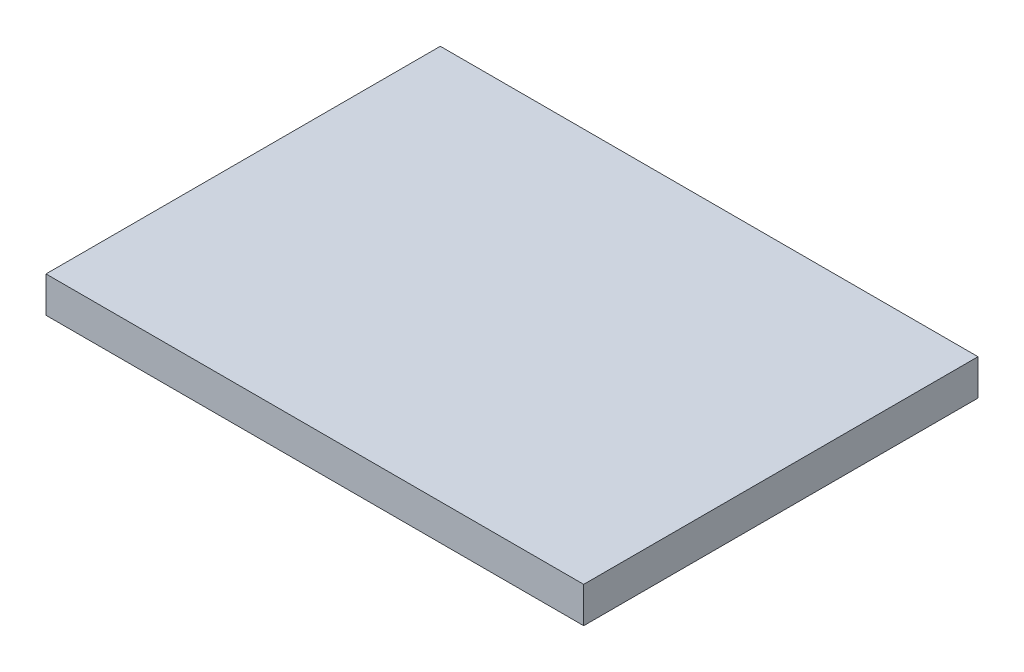
SolidWorks part; units mm, degrees
ref_plane "Front" through (0, 0, 0) normal (0, 0, 1) x (1, 0, 0)
ref_plane "Top" through (0, 0, 0) normal (0, 1, 0) x (1, 0, 0)
ref_plane "Right" through (0, 0, 0) normal (1, 0, 0) x (0, 0, -1)
sketch "Sketch1" plane through (0, 0, 0) normal (0, 1, 0) x (1, 0, 0)
  line L1 (0, 0) -> (150, 0)
  line L2 (0, 0) -> (0, 110)
  line L3 (0, 110) -> (150, 110)
  line L4 (150, 0) -> (150, 110)
  dimension "D1" = 150
  dimension "D2" = 110
extrude "Boss-Extrude1" add sketch "Sketch1" along normal blind 10
ref_plane "Plane1" through (0, 0, -55) normal (0, 0, -1) x (-1, 0, 0)
ref_plane "Plane2" through (75, 0, 0) normal (-1, 0, 0) x (0, 0, 1)
